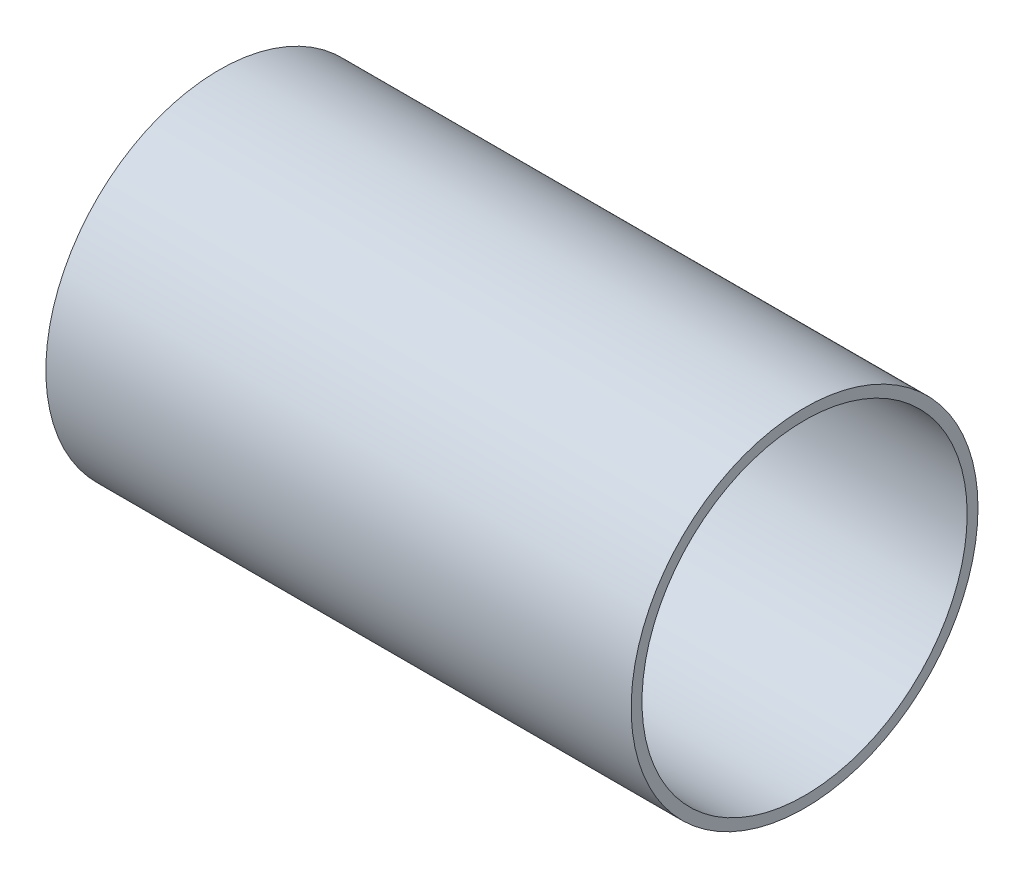
SolidWorks part; units mm, degrees
ref_plane "Front" through (0, 0, 0) normal (0, 0, 1) x (1, 0, 0)
ref_plane "Top" through (0, 0, 0) normal (0, 1, 0) x (1, 0, 0)
ref_plane "Right" through (0, 0, 0) normal (1, 0, 0) x (0, 0, -1)
sketch "Sketch1" plane through (0, 0, 0) normal (1, 0, 0) x (0, 0, -1)
  circle A0 centre (0, 0) radius 10.16
  circle A1 centre (0, 0) radius 9.525
  dimension "D1" = 20.32
  dimension "D2" = 19.05
extrude "Extrude1" add sketch "Sketch1" along normal blind 34.29
